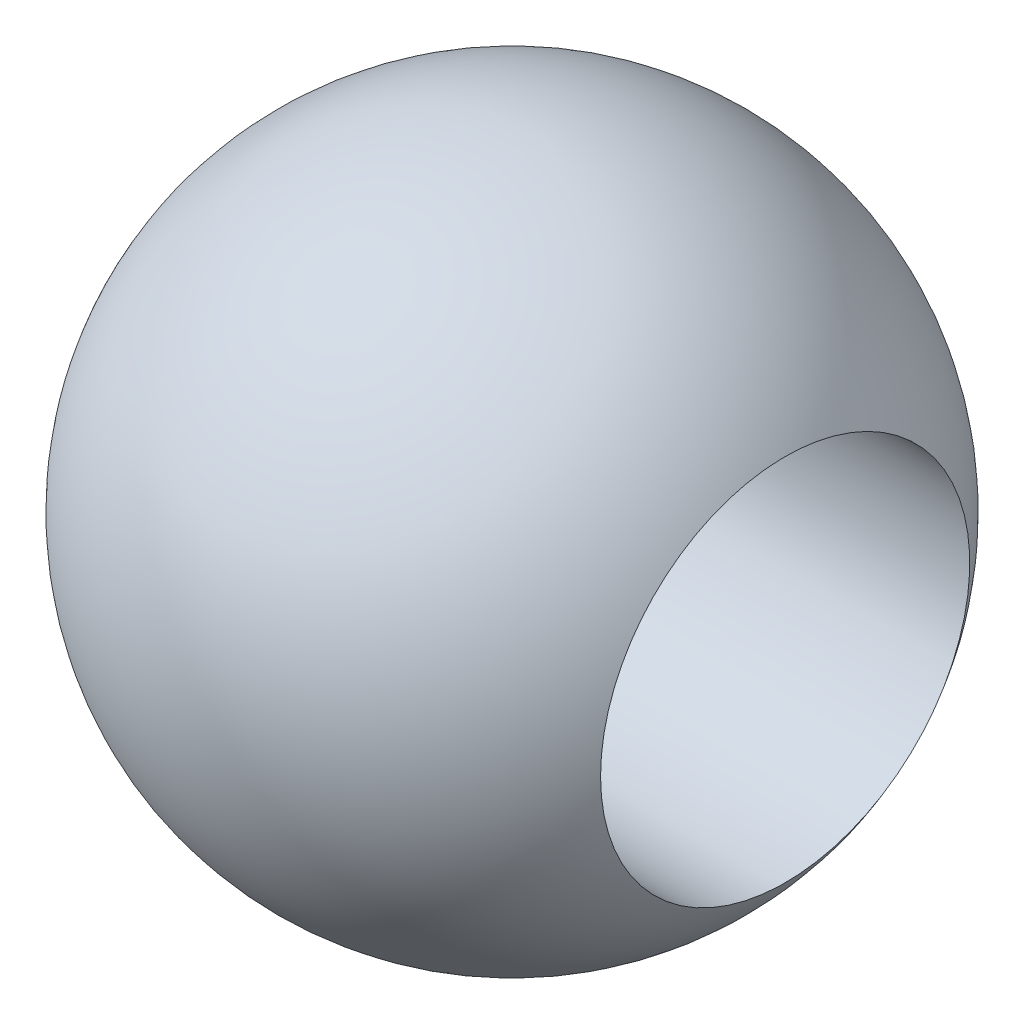
SolidWorks part; units mm, degrees
ref_plane "Płaszczyzna przednia" through (0, 0, 0) normal (0, 0, 1) x (1, 0, 0)
ref_plane "Płaszczyzna górna" through (0, 0, 0) normal (0, 1, 0) x (1, 0, 0)
ref_plane "Płaszczyzna prawa" through (0, 0, 0) normal (1, 0, 0) x (0, 0, -1)
sketch "Szkic2" plane through (0, 0, 0) normal (0, 0, 1) x (1, 0, 0)
  line L0 (0, 63.0851) -> (0, -40.7447) construction
  line L1 (0, 12.5) -> (0, -12.5)
  arc A0 (0, -12.5) -> (0, 12.5) centre (0, 0) cw
  dimension "D1" = 12.5
revolve "Obrót1" add sketch "Szkic2" angle 360 about L0
sketch "Szkic3" plane through (0, 0, 0) normal (1, 0, 0) x (0, 0, -1)
  circle A0 centre (0, 0) radius 7
  dimension "D1" = 14
extrude "Wytnij-wyciągnięcie1" cut sketch "Szkic3" against normal through all and the other way through all
